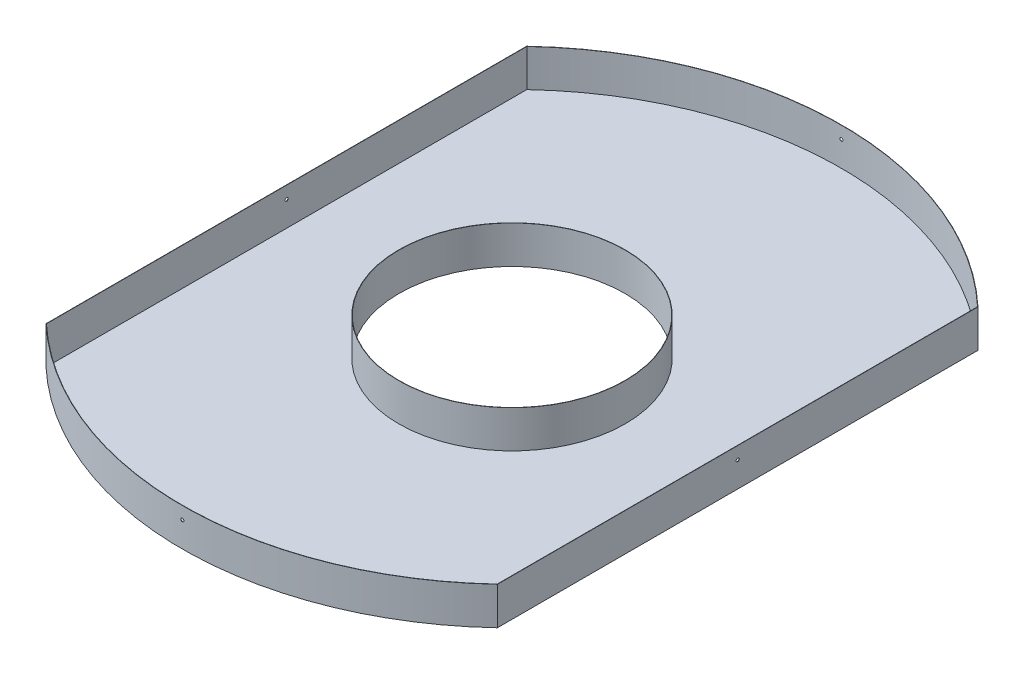
SolidWorks part; units mm, degrees
material "1345 Alloy"
ref_plane "Front Plane" through (0, 0, 0) normal (0, 0, 1) x (1, 0, 0)
ref_plane "Top Plane" through (0, 0, 0) normal (0, 1, 0) x (1, 0, 0)
ref_plane "Right Plane" through (0, 0, 0) normal (1, 0, 0) x (0, 0, -1)
sketch "Sketch1" plane through (0, 0, 0) normal (0, 1, 0) x (1, 0, 0)
  circle A0 centre (0, 0) radius 1750
extrude "Boss-Extrude1" add sketch "Sketch1" along normal blind 500
sketch "Sketch2" plane through (0, 500, 0) normal (0, 1, 0) x (1, 0, 0)
  circle A0 centre (0, 0) radius 900
extrude "Cut-Extrude2" cut sketch "Sketch2" against normal blind 300
sketch "Sketch10" plane through (0, 500, 0) normal (0, 1, 0) x (1, 0, 0)
  line L1 (-2200.588, -2811.5432) -> (2200.588, -2811.5432)
  line L2 (-2200.588, -2811.5432) -> (-2200.588, 2811.5432)
  line L3 (-2200.588, 2811.5432) -> (2200.588, 2811.5432)
  line L4 (2200.588, -2811.5432) -> (2200.588, 2811.5432)
  line L5 (-2200.588, -2811.5432) -> (2200.588, 2811.5432) construction
  line L6 (-2200.588, 2811.5432) -> (2200.588, -2811.5432) construction
  line L7 (-1198.0599, -2169.9586) -> (1198.0599, -2169.9586)
  line L8 (-1198.0599, -2169.9586) -> (-1198.0599, 2169.9586)
  line L9 (-1198.0599, 2169.9586) -> (1198.0599, 2169.9586)
  line L10 (1198.0599, -2169.9586) -> (1198.0599, 2169.9586)
  line L11 (-1198.0599, -2169.9586) -> (1198.0599, 2169.9586) construction
  line L12 (-1198.0599, 2169.9586) -> (1198.0599, -2169.9586) construction
  point P0 (0, 0)
  point P6 (0, 0)
extrude "Cut-Extrude10" cut sketch "Sketch10" against normal through all both and the other way through all
sketch "Sketch3" plane through (0, 0, 0) normal (0, -1, 0) x (1, 0, 0)
  circle A0 centre (0, 0) radius 600
extrude "Cut-Extrude3" cut sketch "Sketch3" against normal blind 300
shell "Shell1" thickness 1.5
sketch "Sketch11" plane through (0, 200, 0) normal (0, 1, 0) x (1, 0, 0)
  line L1 (-1546.6788, 2430.4952) -> (1546.6788, 2430.4952)
  line L2 (-1546.6788, 2430.4952) -> (-1546.6788, -2430.4952)
  line L3 (-1546.6788, -2430.4952) -> (1546.6788, -2430.4952)
  line L4 (1546.6788, 2430.4952) -> (1546.6788, -2430.4952)
  line L5 (-1546.6788, 2430.4952) -> (1546.6788, -2430.4952) construction
  line L6 (-1546.6788, -2430.4952) -> (1546.6788, 2430.4952) construction
  point P0 (0, 0)
extrude "Cut-Extrude11" cut sketch "Sketch11" along normal through all
ref_plane "Plane1" through (0, 0, 2000) normal (0, 0, 1) x (1, 0, 0)
sketch "Sketch7" plane through (0, 0, 2000) normal (0, 0, 1) x (1, 0, 0)
  circle A0 centre (0, 133.8976) radius 8.382
extrude "Cut-Extrude6" cut sketch "Sketch7" against normal blind 900
pattern_circular "CirPattern1" count 4 over 360 about axis through (0, 500, 0) along (0, -1, 0) of "Cut-Extrude6"
ref_plane "Plane2" through (-1237.4369, 0, 1237.4369) normal (-0.7071, 0, 0.7071) x (0, -1, 0)
sketch "Sketch12" plane through (-1198.0599, 0, 0) normal (-1, 0, 0) x (0, 0, 1)
  line L0 (-828.0253, 88.1097) -> (-805.4725, 65.5569)
  line L1 (-805.4725, 65.5569) -> (-773.578, 65.5569)
  line L2 (-773.578, 65.5569) -> (-751.0253, 88.1097)
  line L3 (-751.0253, 88.1097) -> (-751.0253, 120.0042)
  line L4 (-751.0253, 120.0042) -> (-773.578, 142.5569)
  line L5 (-773.578, 142.5569) -> (-805.4725, 142.5569)
  line L6 (-805.4725, 142.5569) -> (-828.0253, 120.0042)
  line L7 (-828.0253, 120.0042) -> (-828.0253, 88.1097)
  circle A0 centre (-789.5253, 104.0569) radius 38.5 construction
extrude "Cut-Extrude13" [suppressed] cut sketch "Sketch12" against normal blind 10
sketch "Sketch13" plane through (0, 200, 0) normal (0, 1, 0) x (1, 0, 0)
  circle A0 centre (0, 0) radius 901.5 construction
  circle A1 centre (0, 0) radius 901.5
  circle A2 centre (0, 0) radius 601.5
extrude "Cut-Extrude14" cut sketch "Sketch13" against normal blind 10
